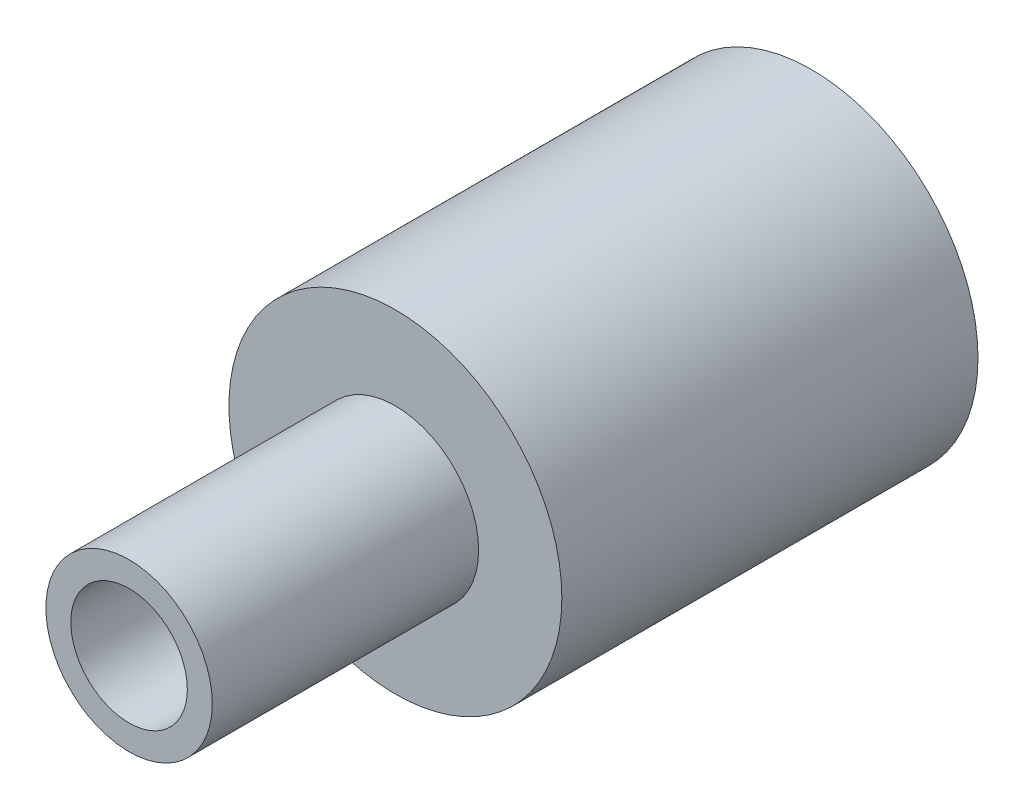
SolidWorks part; units mm, degrees
material "ABS PC"
ref_plane "Front Plane" through (0, 0, 0) normal (0, 0, 1) x (1, 0, 0)
ref_plane "Top Plane" through (0, 0, 0) normal (0, 1, 0) x (1, 0, 0)
ref_plane "Right Plane" through (0, 0, 0) normal (1, 0, 0) x (0, 0, -1)
sketch "Sketch1" plane through (0, 0, 0) normal (0, 0, 1) x (1, 0, 0)
  circle A0 centre (0, 0) radius 10
  dimension "D1" = 20
extrude "Boss-Extrude1" add sketch "Sketch1" along normal blind 41
sketch "Sketch2" plane through (0, 0, 0) normal (0, 0, -1) x (-1, 0, 0)
  circle A0 centre (0, 0) radius 5
  dimension "D1" = 10
extrude "Cut-Extrude1" cut sketch "Sketch2" against normal blind 10
sketch "Sketch3" plane through (0, 0, 41) normal (0, 0, 1) x (1, 0, 0)
  circle A0 centre (0, 0) radius 5
  dimension "D1" = 10
extrude "Cut-Extrude2" cut sketch "Sketch3" against normal blind 16 flip side to cut
sketch "Sketch4" plane through (0, 0, 41) normal (0, 0, 1) x (1, 0, 0)
  circle A0 centre (0, 0) radius 3.5
  dimension "D1" = 7
extrude "Cut-Extrude3" cut sketch "Sketch4" against normal blind 12
